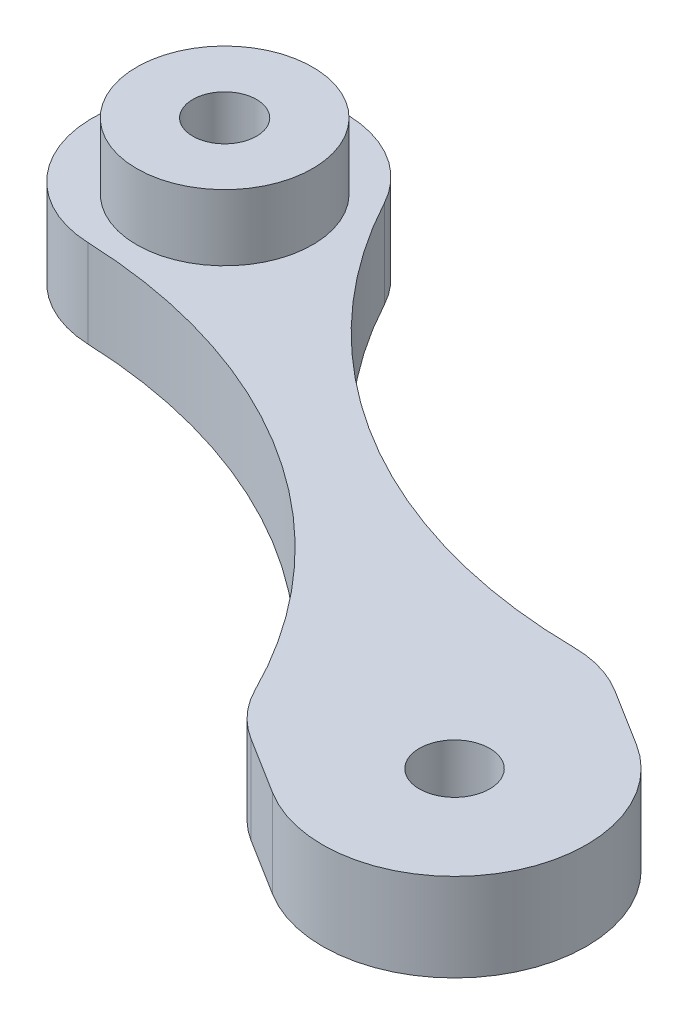
SolidWorks part; units mm, degrees
ref_plane "Front Plane" through (0, 0, 0) normal (0, 0, 1) x (1, 0, 0)
ref_plane "Top Plane" through (0, 0, 0) normal (0, 1, 0) x (1, 0, 0)
ref_plane "Right Plane" through (0, 0, 0) normal (1, 0, 0) x (0, 0, -1)
sketch "Sketch1" plane through (0, 0, 0) normal (0, 1, 0) x (1, 0, 0)
  line L0 (3.1792, 5.0885) -> (31.0292, -12.3115)
  line L1 (0, 0) -> (157.7, 0) construction
  line L2 (0, 0) -> (0, -110.8) construction
  line L3 (0, -110.8) -> (157.7, -110.8) construction
  line L4 (157.7, 0) -> (157.7, -110.8) construction
  line L5 (27.85, -17.4) -> (129.85, -17.4) construction
  line L6 (27.85, -17.4) -> (27.85, -93.4) construction
  line L7 (27.85, -93.4) -> (129.85, -93.4) construction
  line L8 (129.85, -17.4) -> (129.85, -93.4) construction
  line L9 (-3.1792, -5.0885) -> (24.6708, -22.4885)
  arc A0 (21.85, -17.4) -> (26.8245, -11.4883) centre (27.85, -17.4) ccw
  arc A1 (6, 0) -> (-5.5477, -2.2855) centre (0, 0) ccw
  circle A2 centre (0, 0) radius 1.45
  circle A3 centre (27.85, -17.4) radius 1.6
  circle A4 centre (0, 0) radius 6
  circle A5 centre (27.85, -17.4) radius 6
  dimension "D7" = 12
  dimension "D8" = 12
  dimension "D9" = 2.9
  dimension "D10" = 3.2
  dimension "D1" = 110.8
  dimension "D2" = 157.7
  dimension "D3" = 76
  dimension "D4" = 102
  dimension "D5" = 27.85
  dimension "D6" = 17.4
extrude "Boss-Extrude1" add sketch "Sketch1" along normal blind 4 contours A1 A4 A2 | A5 A0 L0 A1 A4 L9 | A0 A5 A3
sketch "Sketch2" plane through (0, 4, 0) normal (0, 1, 0) x (1, 0, 0)
  circle A0 centre (0, 0) radius 1.45
  circle A1 centre (0, 0) radius 4
  dimension "D1" = 8
  dimension "D2" = 2.9
extrude "Boss-Extrude2" add sketch "Sketch2" along normal blind 3
sketch "Sketch3" plane through (0, 4, 0) normal (0, 1, 0) x (1, 0, 0)
  line L0 (32.9385, -20.5792) -> (12.5107, -7.8164) construction
  circle A0 centre (-2.15, -30) radius 25
  circle A1 centre (27.85, -17.4) radius 1.6 construction
  arc A2 (24.6708, -22.4885) -> (31.0292, -12.3115) centre (27.85, -17.4) ccw construction
  circle A3 centre (26.0193, 15.0871) radius 25
  dimension "D3" = 50
  dimension "D1" = 30
  dimension "D2" = 30
extrude "Cut-Extrude1" cut sketch "Sketch3" against normal blind 10
fillet "Fillet1" radius 5 4 edges at (27.1492, 2, 9.8874) (20.7909, 2, 20.0644) (3.0792, 2, -5.1496) (-3.2779, 2, 5.0255)
equation "\"D5@Sketch1\"=(\"D2@Sketch1\"-\"D4@Sketch1\")/2"
equation "\"D6@Sketch1\"=(\"D1@Sketch1\"-\"D3@Sketch1\")/2"
